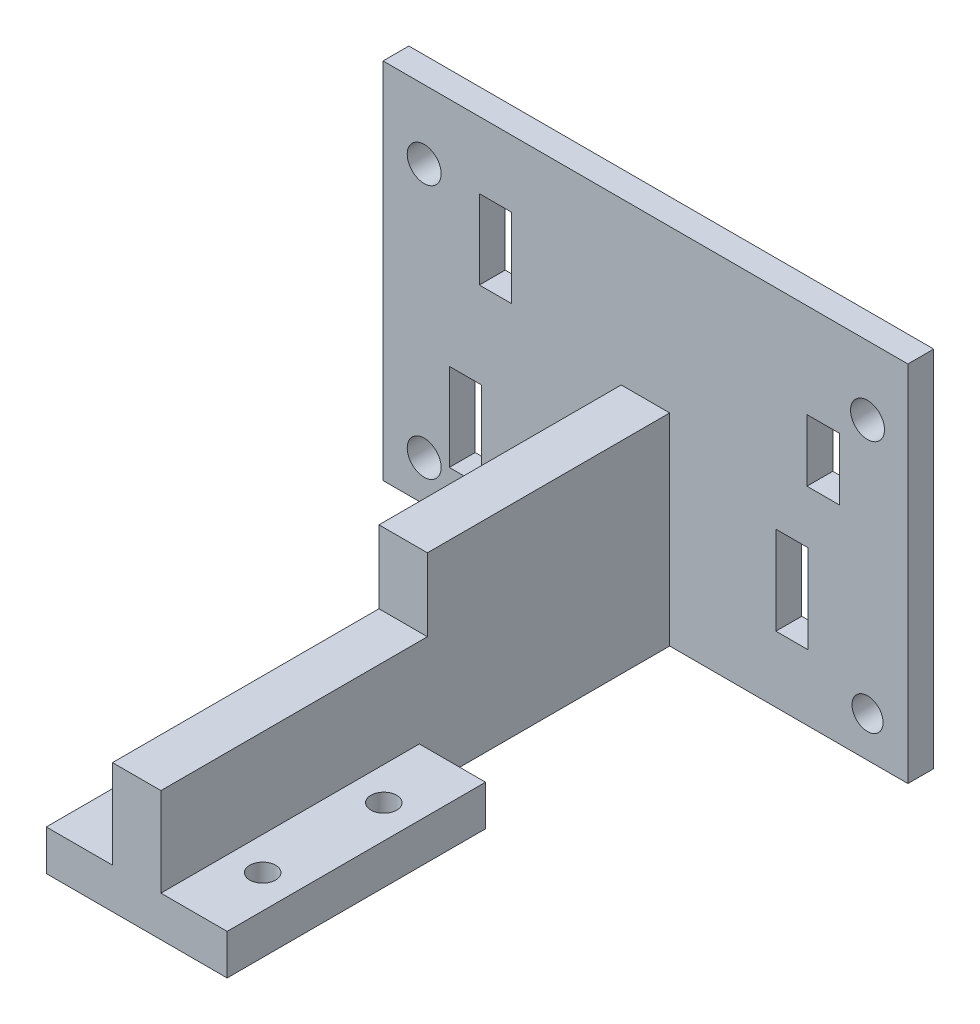
SolidWorks part; units mm, degrees
ref_plane "前视基准面" through (0, 0, 0) normal (0, 0, 1) x (1, 0, 0)
ref_plane "上视基准面" through (0, 0, 0) normal (0, 1, 0) x (1, 0, 0)
ref_plane "右视基准面" through (0, 0, 0) normal (1, 0, 0) x (0, 0, -1)
sketch "草图1" plane through (0, 0, 0) normal (0, 1, 0) x (1, 0, 0)
  line L0 (-55, 0) -> (55, 0) construction
  line L2 (-4.1, -16) -> (4.1, -16)
  line L3 (-4.1, -16) -> (-4.1, 16)
  line L4 (-4.1, 16) -> (4.1, 16)
  line L5 (4.1, -16) -> (4.1, 16)
  line L6 (-4.1, -16) -> (4.1, 16) construction
  line L7 (-4.1, 16) -> (4.1, -16) construction
  circle A0 centre (0, 7.5) radius 1.6
  circle A1 centre (0, -7.5) radius 1.6
  point P6 (0, 0)
  dimension "D1" = 3.2
  dimension "D2" = 15
  dimension "D3" = 8.2
  dimension "D4" = 32
extrude "凸台-拉伸1" add sketch "草图1" along normal blind 5
sketch "草图2" plane through (0, 0, 0) normal (0, 1, 0) x (1, 0, 0)
  line L1 (4.1, 47) -> (10.1, 47)
  line L2 (4.1, 47) -> (4.1, -16)
  line L3 (4.1, -16) -> (10.1, -16)
  line L4 (10.1, 47) -> (10.1, -16)
  line L8 (-4.1, -16) -> (4.1, -16) construction
  line L9 (4.1, -16) -> (4.1, 16) construction
  dimension "D1" = 63
  dimension "D2" = 6
extrude "凸台-拉伸2" add sketch "草图2" along normal blind 25
sketch "草图3" plane through (0, 0, -47) normal (0, 0, -1) x (-1, 0, 0)
  line L0 (-10.1, 12.5) -> (-4.1, 12.5) construction
  line L1 (-10.1, 25) -> (-10.1, 0) construction
  line L2 (-4.1, 25) -> (-4.1, 0) construction
  line L3 (-7.1, 25) -> (-7.1, 0) construction
  line L4 (-10.1, 25) -> (-4.1, 25) construction
  line L5 (-10.1, 0) -> (-4.1, 0) construction
  line L7 (-39.6, 0) -> (25.4, 0)
  line L8 (-39.6, 0) -> (-39.6, 45)
  line L9 (-39.6, 45) -> (25.4, 45)
  line L10 (25.4, 0) -> (25.4, 45)
  line L11 (-39.6, 0) -> (25.4, 45) construction
  line L12 (-39.6, 45) -> (25.4, 0) construction
  point P12 (-7.1, 22.5)
  dimension "D1" = 65
  dimension "D2" = 45
extrude "凸台-拉伸3" add sketch "草图3" along normal blind 3.2
sketch "草图4" plane through (0, 0, -50.2) normal (0, 0, -1) x (-1, 0, 0)
  line L0 (-39.6, 45) -> (-39.6, 0) construction
  line L1 (-39.6, 0) -> (25.4, 0) construction
  circle A0 centre (-34.6, 5) radius 1.9225
  circle A1 centre (20.3, 5) radius 2.1
  circle A2 centre (-34.6, 36.5) radius 2.1
  circle A3 centre (20.3, 36.5) radius 2.1
  dimension "D1" = 54.9
  dimension "D2" = 5
  dimension "D3" = 4.2
  dimension "D4" = 5
  dimension "D5" = 31.5
  dimension "D6" = 4.2
  dimension "D7" = 4.2
extrude "切除-拉伸1" cut sketch "草图4" against normal blind 13.2
sketch "草图7" plane through (0, 0, -50.2) normal (0, 0, -1) x (-1, 0, 0)
  line L1 (-31.1003, 25.6411) -> (-27.1003, 25.6411)
  line L2 (-31.1003, 25.6411) -> (-31.1003, 33.3238)
  line L3 (-31.1003, 33.3238) -> (-27.1003, 33.3238)
  line L4 (-27.1003, 25.6411) -> (-27.1003, 33.3238)
  line L5 (-31.1003, 25.6411) -> (-27.1003, 33.3238) construction
  line L6 (-31.1003, 33.3238) -> (-27.1003, 25.6411) construction
  line L7 (-27.2523, 8.1697) -> (-23.2523, 8.1697)
  line L8 (-27.2523, 8.1697) -> (-27.2523, 19.1103)
  line L9 (-27.2523, 19.1103) -> (-23.2523, 19.1103)
  line L10 (-23.2523, 8.1697) -> (-23.2523, 19.1103)
  line L11 (-27.2523, 8.1697) -> (-23.2523, 19.1103) construction
  line L12 (-27.2523, 19.1103) -> (-23.2523, 8.1697) construction
  line L13 (9.4655, 26.9347) -> (13.4655, 26.9347)
  line L14 (9.4655, 26.9347) -> (9.4655, 36.7335)
  line L15 (9.4655, 36.7335) -> (13.4655, 36.7335)
  line L16 (13.4655, 26.9347) -> (13.4655, 36.7335)
  line L17 (9.4655, 26.9347) -> (13.4655, 36.7335) construction
  line L18 (9.4655, 36.7335) -> (13.4655, 26.9347) construction
  line L19 (13.1889, 5.5088) -> (17.1889, 5.5088)
  line L20 (13.1889, 5.5088) -> (13.1889, 16.3525)
  line L21 (13.1889, 16.3525) -> (17.1889, 16.3525)
  line L22 (17.1889, 5.5088) -> (17.1889, 16.3525)
  line L23 (13.1889, 5.5088) -> (17.1889, 16.3525) construction
  line L24 (13.1889, 16.3525) -> (17.1889, 5.5088) construction
  point P0 (-29.1003, 29.4824)
  point P5 (-25.2523, 13.64)
  point P10 (15.1889, 10.9306)
  point P11 (11.4655, 31.8341)
  dimension "D1" = 4
  dimension "D2" = 4
  dimension "D3" = 4
extrude "切除-拉伸2" cut sketch "草图7" against normal blind 13.2
ref_plane "基准面4" through (7.1, 0, 0) normal (-1, 0, 0) x (0, 0, 1)
mirror "镜向1" about plane through (7.1, 0, 0) normal (-1, 0, 0) of "凸台-拉伸1"
sketch "草图8" plane through (4.1, 0, 0) normal (-1, 0, 0) x (0, 0, 1)
  line L1 (16, 25) -> (-17, 25)
  line L2 (16, 25) -> (16, 16)
  line L3 (16, 16) -> (-17, 16)
  line L4 (-17, 25) -> (-17, 16)
  dimension "D1" = 9
  dimension "D2" = 33
extrude "切除-拉伸3" cut sketch "草图8" against normal blind 13.2
